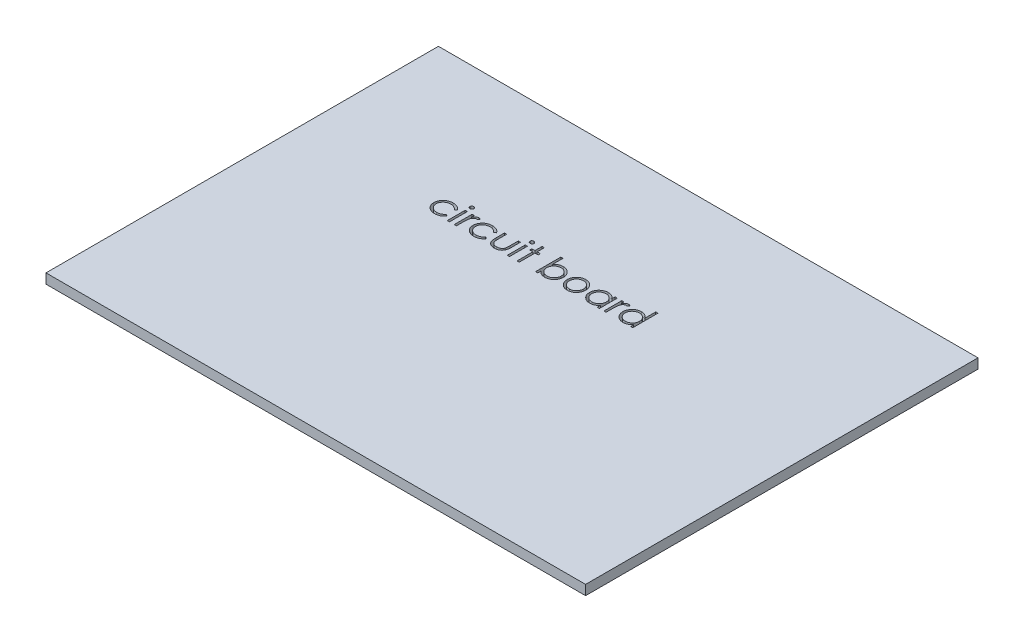
SolidWorks part; units mm, degrees
ref_plane "Front Plane" through (0, 0, 0) normal (0, 0, 1) x (1, 0, 0)
ref_plane "Top Plane" through (0, 0, 0) normal (0, 1, 0) x (1, 0, 0)
ref_plane "Right Plane" through (0, 0, 0) normal (1, 0, 0) x (0, 0, -1)
sketch "Sketch1" plane through (0, 0, 0) normal (0, 1, 0) x (1, 0, 0)
  line L1 (0, 0) -> (69.85, 0)
  line L2 (0, 0) -> (0, 50.8)
  line L3 (0, 50.8) -> (69.85, 50.8)
  line L4 (69.85, 0) -> (69.85, 50.8)
  dimension "D1" = 69.85
  dimension "D2" = 50.8
extrude "Boss-Extrude1" add sketch "Sketch1" along normal blind 1.27 contours L1 L4 L3 L2
sketch "Sketch2" plane through (0, 1.27, 0) normal (0, 1, 0) x (1, 0, 0)
  text T0 "circuit board"
extrude "Cut-Extrude1" cut sketch "Sketch2" against normal through all
